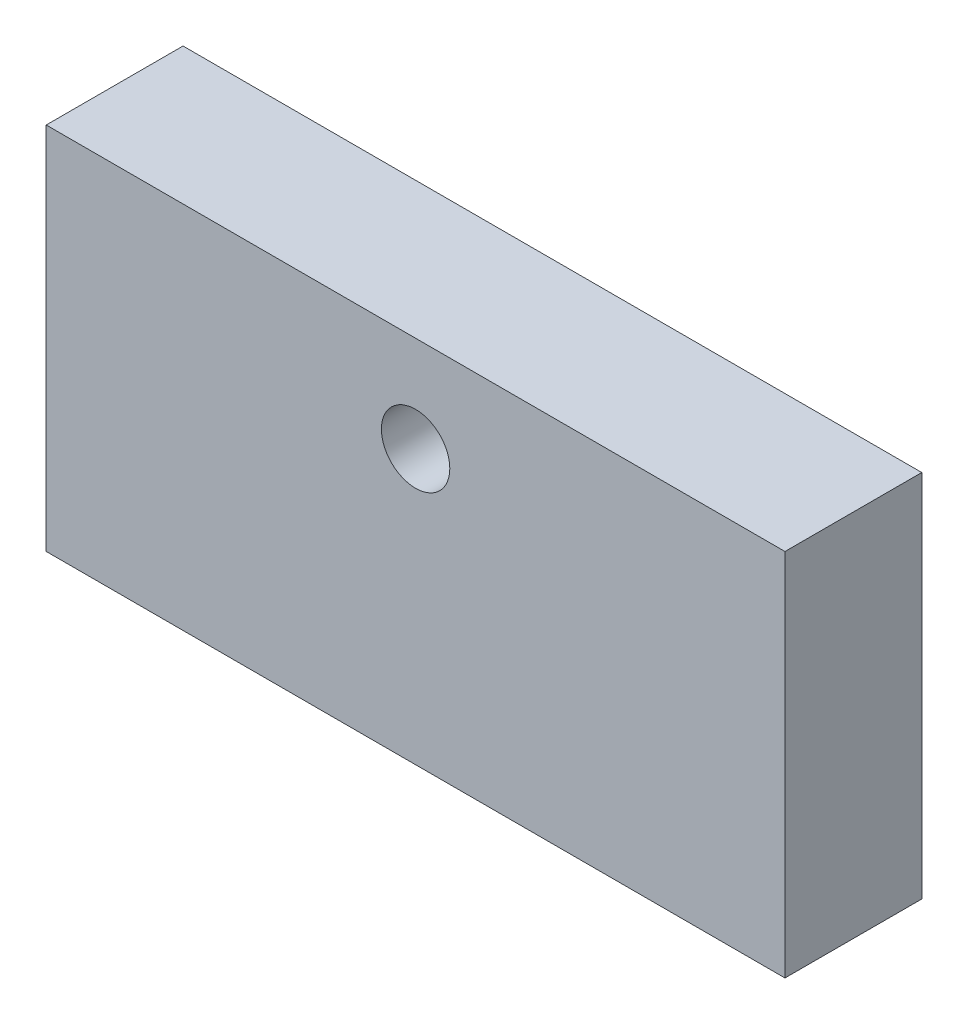
SolidWorks part; units mm, degrees
material "SKD11淬火HRC56-60"
ref_plane "前基準面" through (0, 0, 0) normal (0, 0, 1) x (1, 0, 0)
ref_plane "上基準面" through (0, 0, 0) normal (0, 1, 0) x (1, 0, 0)
ref_plane "右基準面" through (0, 0, 0) normal (1, 0, 0) x (0, 0, -1)
sketch "草图1" plane through (0, 0, 0) normal (0, 0, 1) x (1, 0, 0)
  line L1 (0, 0) -> (54, 0)
  line L2 (0, 0) -> (0, 27)
  line L3 (0, 27) -> (54, 27)
  line L4 (54, 0) -> (54, 27)
  dimension "D1" = 54
  dimension "D2" = 27
extrude "凸台-拉伸1" add sketch "草图1" along normal blind 10
hole_wizard "M6 螺纹孔1" positions "草图3" profile "草图2" tap size "M6" standard "ISO"
sketch "草图3" plane through (0, 0, 10) normal (0, 0, 1) x (1, 0, 0)
  line L0 (27, 0) -> (27, 27) construction
  line L1 (0, 0) -> (54, 0) construction
  line L2 (54, 27) -> (0, 27) construction
  point P0 (27, 20)
  dimension "D1" = 20
sketch "草图2" plane through (27, 20, 10) normal (1, 0, 0) x (0, -1, 0)
  line L0 (0, 0) -> (0, 16.5022)
  line L1 (0, 16.5022) -> (2.5, 15)
  line L2 (2.5, 15) -> (2.5, 0)
  line L5 (2.5, 0) -> (0, 0)
  line L10 (0, 16.5022) -> (-2.5, 15) construction
  line L11 (0, -6.35) -> (0, 107.95) construction
  dimension "螺纹孔钻头直径" = 5
  dimension "螺纹孔钻头深度" = 15
  dimension "导头角度" = 118
cosmetic thread "孔螺蚊线1"
